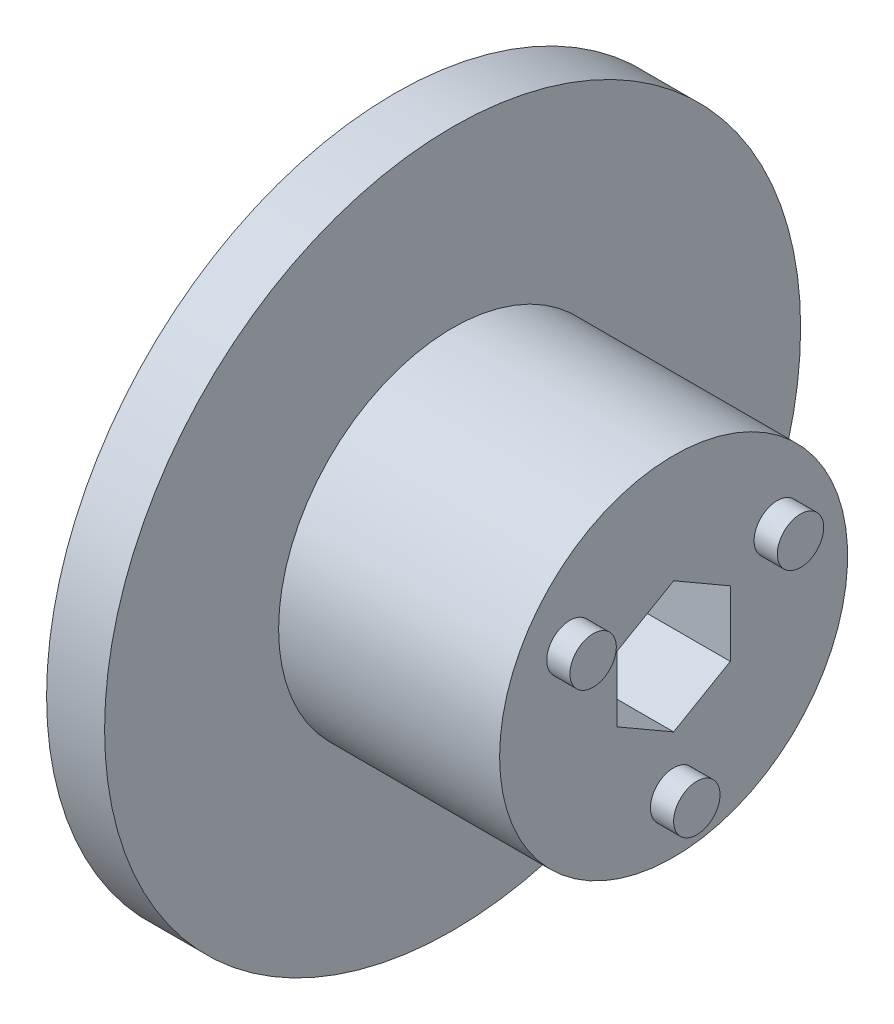
SolidWorks part; units mm, degrees
ref_plane "Front Plane" through (0, 0, 0) normal (0, 0, 1) x (1, 0, 0)
ref_plane "Top Plane" through (0, 0, 0) normal (0, 1, 0) x (1, 0, 0)
ref_plane "Right Plane" through (0, 0, 0) normal (1, 0, 0) x (0, 0, -1)
sketch "Sketch2" plane through (0, 0, 0) normal (1, 0, 0) x (0, 0, -1)
  circle A0 centre (0, 0) radius 30
  dimension "D1" = 60
extrude "Boss-Extrude1" add sketch "Sketch2" along normal blind 5
sketch "Sketch3" plane through (5, 0, 0) normal (1, 0, 0) x (0, 0, -1)
  circle A0 centre (0, 0) radius 15
  dimension "D1" = 30
extrude "Boss-Extrude2" add sketch "Sketch3" along normal blind 19.05
sketch "Sketch4" plane through (24.05, 0, 0) normal (1, 0, 0) x (0, 0, -1)
  line L7 (0, 5.6407) -> (-4.885, 2.8204)
  line L8 (-4.885, 2.8204) -> (-4.885, -2.8204)
  line L9 (-4.885, -2.8204) -> (0, -5.6407)
  line L10 (0, -5.6407) -> (4.885, -2.8204)
  line L11 (4.885, -2.8204) -> (4.885, 2.8204)
  line L12 (4.885, 2.8204) -> (0, 5.6407)
  circle A0 centre (0, 0) radius 4.885 construction
  dimension "D1" = 9.77
extrude "Cut-Extrude1" cut sketch "Sketch4" against normal up to surface (24.05 mm away) up to face at (0, 0, -30)
sketch "Sketch5" plane through (24.05, 0, 0) normal (1, 0, 0) x (0, 0, -1)
  line L0 (0, -5.6407) -> (0, -15) construction
  line L1 (4.885, 2.8204) -> (12.9904, 7.5) construction
  line L2 (-4.885, 2.8204) -> (-12.9904, 7.5) construction
  circle A1 centre (0, 0) radius 15 construction
  circle A2 centre (8.9377, 5.1602) radius 2
  circle A3 centre (-8.9377, 5.1602) radius 2
  circle A4 centre (0, -10.3204) radius 2
  dimension "D1" = 4
  dimension "D2" = 4
  dimension "D3" = 4
extrude "Boss-Extrude3" add sketch "Sketch5" along normal blind 2
